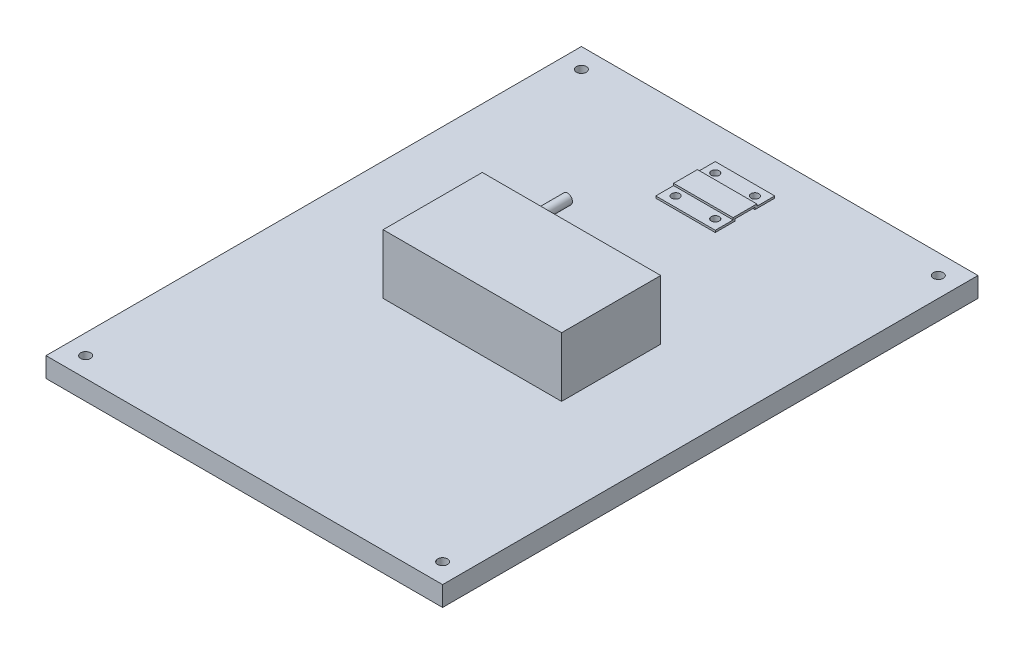
SolidWorks part; units mm, degrees
ref_plane "前视基准面" through (0, 0, 0) normal (0, 0, 1) x (1, 0, 0)
ref_plane "上视基准面" through (0, 0, 0) normal (0, 1, 0) x (1, 0, 0)
ref_plane "右视基准面" through (0, 0, 0) normal (1, 0, 0) x (0, 0, -1)
sketch "草图1" plane through (0, 0, 0) normal (0, 1, 0) x (1, 0, 0)
  line L0 (0, 0) -> (200, 0)
  line L1 (200, 0) -> (200, 270)
  line L2 (200, 270) -> (0, 270)
  line L3 (0, 270) -> (0, 0)
  dimension "D1" = 270
  dimension "D2" = 200
extrude "凸台-拉伸1" add sketch "草图1" along normal blind 10
sketch "草图3" plane through (0, 10, 0) normal (0, 1, 0) x (1, 0, 0)
  line L0 (0, 135) -> (200, 135) construction
  line L1 (10, 10) -> (190, 10) construction
  line L2 (10, 10) -> (10, 260) construction
  line L3 (10, 260) -> (190, 260) construction
  line L4 (190, 10) -> (190, 260) construction
  line L5 (10, 10) -> (190, 260) construction
  line L6 (10, 260) -> (190, 10) construction
  line L7 (0, 270) -> (0, 0) construction
  line L8 (200, 0) -> (200, 270) construction
  line L9 (100, 270) -> (100, 0) construction
  line L10 (200, 270) -> (0, 270) construction
  line L11 (0, 0) -> (200, 0) construction
  circle A0 centre (10, 260) radius 2.5
  circle A1 centre (10, 10) radius 2.5
  circle A2 centre (190, 10) radius 2.5
  circle A3 centre (190, 260) radius 2.5
  point P0 (100, 135)
  dimension "D3" = 5
  dimension "D4" = 5
  dimension "D5" = 5
  dimension "D6" = 5
  dimension "D1" = 180
  dimension "D2" = 250
extrude "切除-拉伸1" cut sketch "草图3" against normal blind 20
ref_plane "基准面1" through (100, 0, 0) normal (1, 0, 0) x (0, 0, -1)
sketch "草图5" plane through (100, 0, 0) normal (1, 0, 0) x (0, 0, -1)
  line L0 (232.5, 10) -> (232.5, 11)
  line L1 (0, 10) -> (270, 10) construction
  line L2 (232.5, 11) -> (242.5, 11)
  line L3 (242.5, 11) -> (242.5, 10)
  line L4 (135, 10) -> (135, 113.4739) construction
  line L8 (232.5, 10) -> (222.5, 10)
  line L9 (222.5, 10) -> (222.5, 11)
  line L10 (222.5, 11) -> (231.5, 11)
  line L11 (231.5, 11) -> (231.5, 12)
  line L12 (231.5, 12) -> (243.5, 12)
  line L13 (243.5, 12) -> (243.5, 11)
  line L14 (243.5, 11) -> (252.5, 11)
  line L15 (252.5, 11) -> (252.5, 10)
  line L16 (252.5, 10) -> (242.5, 10)
  line L17 (270, 10) -> (270, 0) construction
  dimension "D1" = 1
  dimension "D2" = 10
  dimension "D3" = 27.5
  dimension "D4" = 1
  dimension "D5" = 1
  dimension "D6" = 1
  dimension "D7" = 10
  dimension "D8" = 10
  dimension "D9" = 1
  dimension "D10" = 1
sketch "草图6" plane through (0, 10, 0) normal (0, 1, 0) x (1, 0, 0)
  line L0 (150, 110) -> (150, 160)
  line L1 (150, 160) -> (60, 160)
  line L2 (60, 160) -> (60, 110)
  line L3 (60, 110) -> (150, 110)
  line L4 (200, 0) -> (200, 270) construction
  line L6 (200, 135) -> (0, 135) construction
  line L7 (0, 270) -> (0, 0) construction
  dimension "D1" = 90
  dimension "D2" = 50
  dimension "D3" = 50
  dimension "D4" = 25
extrude "凸台-拉伸2" add sketch "草图6" along normal blind 30
sketch "草图7" plane through (0, 0, -160) normal (0, 0, -1) x (-1, 0, 0)
  line L0 (-60, 40) -> (-60, 10) construction
  line L1 (-150, 40) -> (-60, 40) construction
  circle A0 centre (-78, 25) radius 12.5
  dimension "D1" = 25
  dimension "D2" = 18
  dimension "D3" = 15
sketch "草图9" plane through (0, 10, 0) normal (0, 1, 0) x (1, 0, 0)
  line L0 (75, 160) -> (58, 160)
  line L1 (58, 160) -> (58, 185)
  line L2 (58, 185) -> (75, 185)
  line L3 (75, 185) -> (75, 160)
  line L5 (150, 160) -> (60, 160) construction
  line L8 (60, 160) -> (60, 110) construction
  dimension "D1" = 17
  dimension "25" = 25
  dimension "D2" = 15
extrude "切除-拉伸3" cut sketch "草图9" against normal up to next
extrude "凸台-拉伸4" add sketch "草图5" along normal mid plane 30
sketch "草图11" plane through (0, 11, 0) normal (0, 1, 0) x (1, 0, 0)
  line L0 (100, -5.5) -> (100, 5.5) construction
  line L1 (85, 237.5) -> (115, 237.5) construction
  line L2 (85, 243.5) -> (85, 231.5) construction
  line L3 (115, 243.5) -> (115, 231.5) construction
  circle A0 centre (90, 227.5) radius 2
  circle A1 centre (110, 227.5) radius 2
  circle A2 centre (90, 247.5) radius 2
  circle A3 centre (110, 247.5) radius 2
  dimension "D1" = 4
  dimension "D2" = 4
  dimension "D3" = 4
  dimension "D4" = 4
  dimension "D5" = 10
  dimension "D6" = 10
  dimension "D7" = 10
  dimension "D8" = 10
  dimension "D9" = 10
  dimension "D10" = 10
  dimension "D11" = 10
  dimension "D12" = 10
extrude "切除-拉伸4" cut sketch "草图11" against normal blind 8
sketch "草图12" plane through (0, 0, -160) normal (0, 0, -1) x (-1, 0, 0)
  circle A0 centre (-78, 25) radius 2.5
  dimension "D1" = 5
extrude "凸台-拉伸5" add sketch "草图12" along normal blind 25
